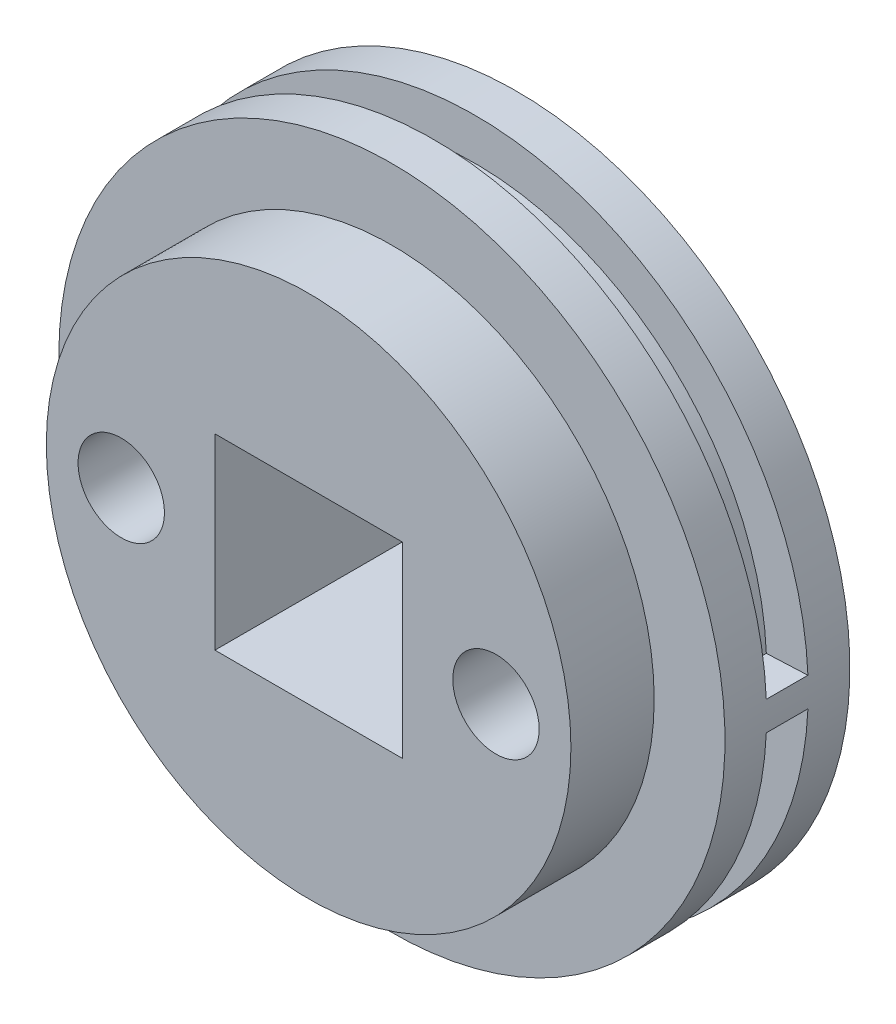
SolidWorks part; units mm, degrees
ref_plane "前视基准面" through (0, 0, 0) normal (0, 0, 1) x (1, 0, 0)
ref_plane "上视基准面" through (0, 0, 0) normal (0, 1, 0) x (1, 0, 0)
ref_plane "右视基准面" through (0, 0, 0) normal (1, 0, 0) x (0, 0, -1)
sketch "草图1" plane through (0, 0, 0) normal (0, 0, 1) x (1, 0, 0)
  circle A0 centre (0, 0) radius 12.6
  dimension "D1" = 25.2
extrude "凸台-拉伸1" add sketch "草图1" along normal blind 4
sketch "草图2" plane through (0, 0, 0) normal (0, 0, -1) x (-1, 0, 0)
  circle A0 centre (0, 0) radius 16
  dimension "D1" = 32
extrude "凸台-拉伸2" add sketch "草图2" along normal blind 6
sketch "草图3" plane through (0, 0, 4) normal (0, 0, 1) x (1, 0, 0)
  circle A0 centre (0, 0) radius 5.5
  dimension "D1" = 11
extrude "凸台-拉伸3" [suppressed] add sketch "草图3" along normal blind 5
sketch "草图4" plane through (0, 0, 4) normal (0, 0, 1) x (1, 0, 0)
  circle A0 centre (-9, 0) radius 2.075
  circle A1 centre (9, 0) radius 2.075
  dimension "D1" = 4.15
  dimension "D2" = 9
  dimension "D3" = 9
extrude "切除-拉伸1" cut sketch "草图4" against normal blind 29
chamfer "倒角1" [suppressed] distance 0.8 angle 45
sketch "草图6" plane through (0, 0, -6) normal (0, 0, -1) x (-1, 0, 0)
  line L1 (-12.5, 3.5) -> (-5.5, 3.5)
  line L2 (-12.5, 3.5) -> (-12.5, -3.5)
  line L3 (-12.5, -3.5) -> (-5.5, -3.5)
  line L4 (-5.5, 3.5) -> (-5.5, -3.5)
  line L5 (-12.5, 3.5) -> (-5.5, -3.5) construction
  line L6 (-12.5, -3.5) -> (-5.5, 3.5) construction
  line L7 (5.5, 3.5) -> (12.5, 3.5)
  line L8 (5.5, 3.5) -> (5.5, -3.5)
  line L9 (5.5, -3.5) -> (12.5, -3.5)
  line L10 (12.5, 3.5) -> (12.5, -3.5)
  line L11 (5.5, 3.5) -> (12.5, -3.5) construction
  line L12 (5.5, -3.5) -> (12.5, 3.5) construction
  point P0 (-9, 0)
  point P6 (9, 0)
  dimension "D1" = 7
  dimension "D2" = 7
  dimension "D3" = 7
  dimension "D4" = 7
extrude "切除-拉伸2" cut sketch "草图6" against normal blind 3.5
sketch "草图7" plane through (0, 0, -6) normal (0, 0, -1) x (-1, 0, 0)
  line L0 (-1.4665, -0.7) -> (1.4665, -0.7)
  arc A0 (1.4665, -0.7) -> (-1.4665, -0.7) centre (0, 0) ccw
  dimension "D1" = 3.25
  dimension "D2" = 0.7
extrude "切除-拉伸3" cut sketch "草图7" against normal blind 31
sketch "草图8" plane through (0, 0, -6) normal (0, 0, -1) x (-1, 0, 0)
  line L0 (-8.4339, 5.373) -> (8.4339, 5.373) construction
  arc A0 (8.4339, 5.373) -> (-8.4339, 5.373) centre (0, 0) ccw construction
  arc A1 (9.2773, 5.9103) -> (-9.2773, 5.9103) centre (0, 0) ccw
  arc A2 (7.5905, 4.8357) -> (-7.5905, 4.8357) centre (0, 0) ccw
  arc A3 (7.5905, 4.8357) -> (9.2773, 5.9103) centre (8.4339, 5.373) ccw
  arc A4 (-9.2773, 5.9103) -> (-7.5905, 4.8357) centre (-8.4339, 5.373) ccw
  point P4 (0, 10)
  dimension "D1" = 1
  dimension "D2" = 10
  dimension "D3" = 115
sketch "草图9" plane through (0, 0, 4) normal (0, 0, 1) x (1, 0, 0)
  line L0 (-1.5, 8) -> (1.5, 8) construction
  line L1 (-1.5, 9.5) -> (1.5, 9.5)
  line L2 (-1.5, 6.5) -> (1.5, 6.5)
  arc A1 (-1.5, 9.5) -> (-1.5, 6.5) centre (-1.5, 8) ccw
  arc A2 (1.5, 6.5) -> (1.5, 9.5) centre (1.5, 8) ccw
  point P2 (0, 8)
  dimension "D1" = 1.5
  dimension "D2" = 3
  dimension "D3" = 8
loft "切除-放样1" [suppressed] cut profiles "草图9", "草图8"
sketch "草图11" plane through (0, 0, -6) normal (0, 0, -1) x (-1, 0, 0)
  line L0 (-3.8971, -2.25) -> (3.8971, -2.25) construction
  line L2 (2, 5.5) -> (-2, 5.5) construction
  line L3 (2, 5.5) -> (2, 3.5) construction
  line L4 (2, 3.5) -> (-2, 3.5) construction
  line L5 (-2, 5.5) -> (-2, 3.5) construction
  line L6 (2, 5.5) -> (-2, 3.5) construction
  line L7 (2, 3.5) -> (-2, 5.5) construction
  arc A0 (-3.8971, -2.25) -> (3.8971, -2.25) centre (0, 0) cw construction
  arc A1 (4.9363, -2.85) -> (-4.9363, -2.85) centre (0, 0) ccw
  arc A2 (2.8579, -1.65) -> (-2.8579, -1.65) centre (0, 0) ccw
  arc A3 (2.8579, -1.65) -> (4.9363, -2.85) centre (3.8971, -2.25) ccw
  arc A4 (-4.9363, -2.85) -> (-2.8579, -1.65) centre (-3.8971, -2.25) ccw
  point P4 (0, 4.5)
  point P11 (0, 4.5)
  dimension "D1" = 4.5
  dimension "D2" = 1.2
  dimension "D3" = 3.3
  dimension "D4" = 2
  dimension "D5" = 4
  dimension "D6" = 120
sketch "草图12" plane through (0, 0, 4) normal (0, 0, 1) x (1, 0, 0)
  line L0 (-1.5, 8) -> (1.5, 8) construction
  line L1 (-1.5, 9.5) -> (1.5, 9.5)
  line L2 (-1.5, 6.5) -> (1.5, 6.5)
  arc A0 (-1.5, 9.5) -> (-1.5, 6.5) centre (-1.5, 8) ccw
  arc A1 (1.5, 6.5) -> (1.5, 9.5) centre (1.5, 8) ccw
  point P2 (0, 8)
  dimension "D1" = 1.5
  dimension "D2" = 3
  dimension "D3" = 8
loft "切除-放样2" [suppressed] cut profiles "草图11", "草图12"
fillet "圆角1" [suppressed] radius 1
fillet "圆角2" [suppressed] radius 0.5
sketch "草图13" plane through (0, 0, -6) normal (0, 0, -1) x (-1, 0, 0)
  line L0 (-2.5152, -3.8514) -> (2.5152, -3.8514) construction
  circle A0 centre (0, 0) radius 3 construction
  arc A1 (-2.5152, -3.8514) -> (2.5152, -3.8514) centre (0, 0) cw construction
  arc A2 (3.062, -4.6887) -> (-3.062, -4.6887) centre (0, 0) ccw
  arc A3 (1.9684, -3.0142) -> (-1.9684, -3.0142) centre (0, 0) ccw
  arc A4 (1.9684, -3.0142) -> (3.062, -4.6887) centre (2.5152, -3.8514) ccw
  arc A5 (-3.062, -4.6887) -> (-1.9684, -3.0142) centre (-2.5152, -3.8514) ccw
  point P5 (0, 4.6)
  dimension "D1" = 6
  dimension "D2" = 1
  dimension "D3" = 4.6
extrude "切除-拉伸5" [suppressed] cut sketch "草图13" against normal blind 31
sketch "草图14" plane through (0, 0, -6) normal (0, 0, -1) x (-1, 0, 0)
  line L0 (5.5, 3.5) -> (5.5, -3.5) construction
  line L1 (-4.5, 4.5) -> (4.5, 4.5)
  line L2 (-4.5, 4.5) -> (-4.5, -4.5)
  line L3 (-4.5, -4.5) -> (4.5, -4.5)
  line L4 (4.5, 4.5) -> (4.5, -4.5)
  line L5 (-4.5, 4.5) -> (4.5, -4.5) construction
  line L6 (-4.5, -4.5) -> (4.5, 4.5) construction
  point P0 (0, 0)
  dimension "D1" = 9
  dimension "D2" = 9
  dimension "D3" = 1
extrude "切除-拉伸6" cut sketch "草图14" against normal blind 10
sketch "草图15" plane through (0, 0, 0) normal (0, 1, 0) x (1, 0, 0)
  line L0 (-16, 6) -> (-16, 0) construction
  line L1 (-18, 2) -> (-14, 2)
  line L2 (-18, 2) -> (-18, 4)
  line L3 (-18, 4) -> (-14, 4)
  line L4 (-14, 2) -> (-14, 4)
  line L5 (-18, 2) -> (-14, 4) construction
  line L6 (-18, 4) -> (-14, 2) construction
  line L7 (16, 6) -> (-16, 6) construction
  line L8 (-16, 0) -> (16, 0) construction
  point P0 (-16, 3)
  dimension "D1" = 3
  dimension "D2" = 3
  dimension "D3" = 2
  dimension "D4" = 4
revolve "切除-旋转1" cut sketch "草图15" angle 177.5 about axis through (0, 0, -6) along (0, 0, 1)
mirror "镜向1" about plane through (0, 0, 0) normal (0, 1, 0) of "切除-旋转1"
